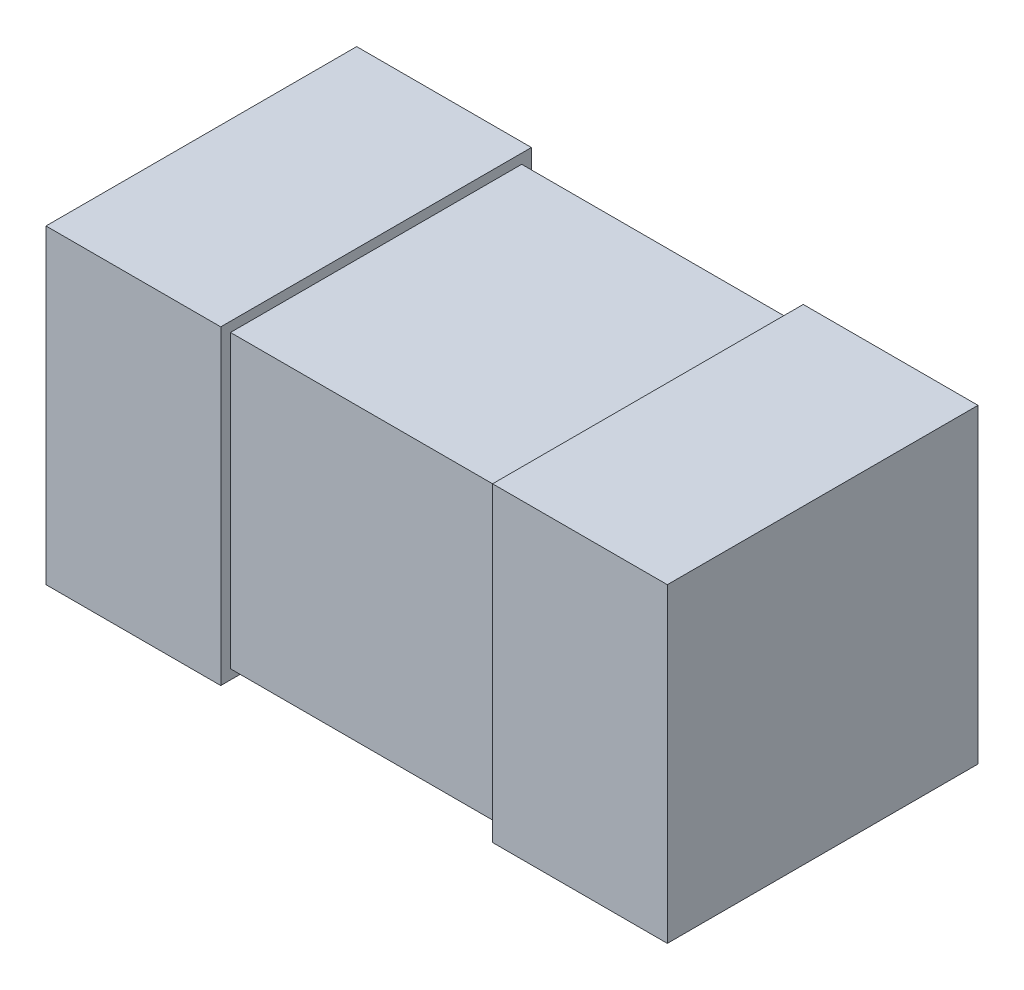
SolidWorks part; units mm, degrees
ref_plane "Front" through (0, 0, 0) normal (0, 0, 1) x (1, 0, 0)
ref_plane "Top" through (0, 0, 0) normal (0, 1, 0) x (1, 0, 0)
ref_plane "Right" through (0, 0, 0) normal (1, 0, 0) x (0, 0, -1)
sketch "Sketch1" plane through (0, 0, 0) normal (0, 1, 0) x (1, 0, 0)
  line L1 (0, 0) -> (0.9, 0)
  line L2 (0, 0) -> (0, 1.6)
  line L3 (0, 1.6) -> (0.9, 1.6)
  line L4 (0.9, 0) -> (0.9, 1.6)
  line L5 (2.3, 0) -> (3.2, 0)
  line L6 (2.3, 0) -> (2.3, 1.6)
  line L7 (2.3, 1.6) -> (3.2, 1.6)
  line L8 (3.2, 0) -> (3.2, 1.6)
  dimension "D1" = 3.2
  dimension "D2" = 0.9
  dimension "D3" = 0.9
  dimension "D4" = 1.6
  dimension "D5" = 1.6
extrude "Boss-Extrude1" add sketch "Sketch1" along normal blind 1.6
sketch "Sketch2" plane through (0.9, 0, 0) normal (1, 0, 0) x (0, 0, -1)
  line L0 (0, 1.6) -> (0, 0) construction
  line L1 (0.05, 1.55) -> (1.55, 1.55)
  line L2 (0.05, 1.55) -> (0.05, 0.05)
  line L3 (0.05, 0.05) -> (1.55, 0.05)
  line L4 (1.55, 1.55) -> (1.55, 0.05)
  line L5 (0, 1.6) -> (1.6, 1.6) construction
  dimension "D1" = 1.5
  dimension "D2" = 0.05
  dimension "D3" = 0.05
  dimension "D4" = 1.5
extrude "Boss-Extrude2" add sketch "Sketch2" along normal up to next
